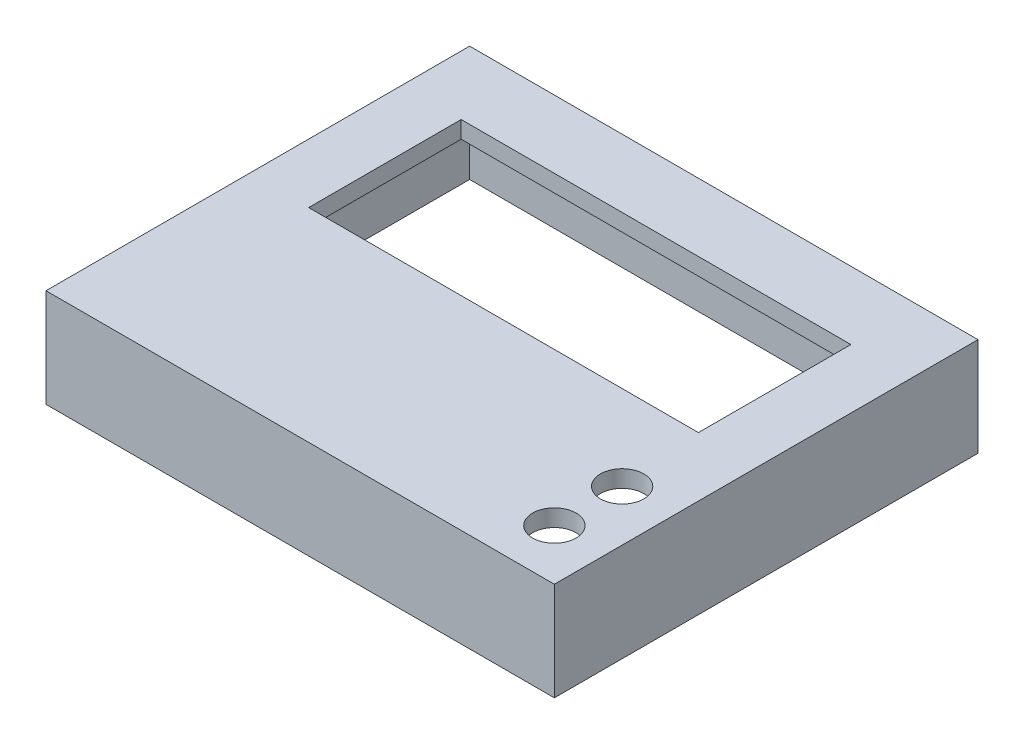
SolidWorks part; units mm, degrees
ref_plane "Front Plane" through (0, 0, 0) normal (0, 0, 1) x (1, 0, 0)
ref_plane "Top Plane" through (0, 0, 0) normal (0, 1, 0) x (1, 0, 0)
ref_plane "Right Plane" through (0, 0, 0) normal (1, 0, 0) x (0, 0, -1)
sketch "Sketch1" plane through (0, 0, 0) normal (0, 1, 0) x (1, 0, 0)
  line L1 (36.5125, 14.2875) -> (-36.5125, 14.2875)
  line L2 (36.5125, 14.2875) -> (36.5125, -14.2875)
  line L3 (36.5125, -14.2875) -> (-36.5125, -14.2875)
  line L4 (-36.5125, 14.2875) -> (-36.5125, -14.2875)
  line L5 (36.5125, 14.2875) -> (-36.5125, -14.2875) construction
  line L6 (36.5125, -14.2875) -> (-36.5125, 14.2875) construction
  line L7 (47.625, 26.9875) -> (-47.625, 26.9875)
  line L8 (47.625, 26.9875) -> (47.625, -52.3875)
  line L9 (47.625, -52.3875) -> (-47.625, -52.3875)
  line L10 (-47.625, 26.9875) -> (-47.625, -52.3875)
  line L11 (47.625, 26.9875) -> (-47.625, -52.3875) construction
  line L12 (47.625, -52.3875) -> (-47.625, 26.9875) construction
  point P0 (0, 0)
  point P5 (0, -12.7)
  point P11 (0, 0)
  dimension "D1" = 73.025
  dimension "D2" = 28.575
  dimension "D3" = 95.25
  dimension "D4" = 38.1
  dimension "D5" = 12.7
extrude "Boss-Extrude1" add sketch "Sketch1" along normal blind 3.2
sketch "Sketch2" plane through (0, 0, 0) normal (0, -1, 0) x (1, 0, 0)
  line L4 (-47.625, 52.3875) -> (-47.625, -26.9875)
  line L5 (-47.625, -26.9875) -> (47.625, -26.9875)
  line L6 (47.625, -26.9875) -> (47.625, 52.3875)
  line L7 (47.625, 52.3875) -> (-47.625, 52.3875)
  line L8 (-47.625, 52.3875) -> (-47.625, -26.9875)
  line L9 (-47.625, -26.9875) -> (47.625, -26.9875)
  line L10 (47.625, -26.9875) -> (47.625, 52.3875)
  line L11 (47.625, 52.3875) -> (-47.625, 52.3875)
  dimension "D1" = 0
extrude "Extrude-Thin1" add sketch "Sketch2" along normal blind 15.24 thin thin type one direction reverse wall 3.2
sketch "Sketch3" plane through (0, 3.2, 0) normal (0, 1, 0) x (1, 0, 0)
  line L0 (47.625, -52.3875) -> (47.625, 26.9875) construction
  line L1 (-47.625, -52.3875) -> (47.625, -52.3875) construction
  circle A0 centre (38.1, -30.1625) radius 4.064
  circle A1 centre (38.1, -42.8625) radius 4.064
  point P8 (38.1, -26.3848)
  point P9 (0, 0)
  point P10 (38.1, -23.8125)
  dimension "D1" = 8.128
  dimension "D2" = 9.525
  dimension "D3" = 9.525
  dimension "D4" = 12.7
extrude "Cut-Extrude1" cut sketch "Sketch3" against normal through all
